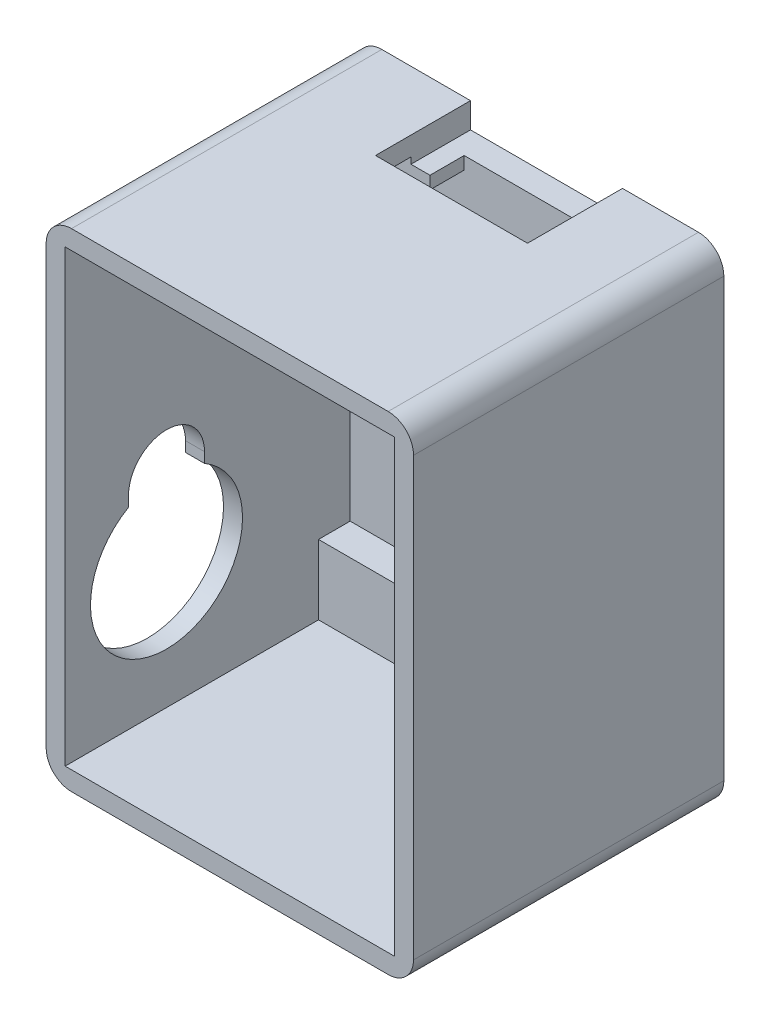
SolidWorks part; units mm, degrees
ref_plane "前视基准面" through (0, 0, 0) normal (0, 0, 1) x (1, 0, 0)
ref_plane "上视基准面" through (0, 0, 0) normal (0, 1, 0) x (1, 0, 0)
ref_plane "右视基准面" through (0, 0, 0) normal (1, 0, 0) x (0, 0, -1)
sketch "草图1" plane through (0, 0, 0) normal (0, 0, 1) x (1, 0, 0)
  line L1 (0, 0) -> (29, 0)
  line L2 (0, 0) -> (0, -38.5)
  line L3 (0, -38.5) -> (29, -38.5)
  line L4 (29, 0) -> (29, -38.5)
extrude "凸台-拉伸1" add sketch "草图1" along normal blind 24
shell "抽壳1" thickness 1.5
sketch "草图2" plane through (0, 0, 0) normal (0, 0, -1) x (-1, 0, 0)
  line L0 (-29, 0) -> (0, 0) construction
  line L1 (-21, 0) -> (-9, 0)
  line L2 (-21, 0) -> (-21, -2)
  line L3 (-21, -2) -> (-9, -2)
  line L4 (-9, 0) -> (-9, -2)
  line L5 (-29, -38.5) -> (-29, 0) construction
  line L6 (0, 0) -> (0, -38.5) construction
  dimension "D1" = 8
  dimension "D2" = 9
sketch "草图5" plane through (27.5, 0, 0) normal (-1, 0, 0) x (0, 0, 1)
  line L0 (24, -1.5) -> (1.5, -1.5) construction
  line L1 (4.2, -1.5) -> (1.5, -1.5)
  line L2 (4.2, -1.5) -> (4.2, -3)
  line L3 (4.2, -3) -> (1.5, -3)
  line L4 (1.5, -1.5) -> (1.5, -3)
  line L5 (1.5, -37) -> (1.5, -1.5) construction
sketch "草图6" plane through (1.5, 0, 0) normal (1, 0, 0) x (0, 0, -1)
  line L0 (-24, -1.5) -> (-1.5, -1.5) construction
  line L1 (-4.2, -1.5) -> (-1.5, -1.5)
  line L2 (-4.2, -1.5) -> (-4.2, -3)
  line L3 (-4.2, -3) -> (-1.5, -3)
  line L4 (-1.5, -1.5) -> (-1.5, -3)
  line L5 (-1.5, -1.5) -> (-1.5, -37) construction
sketch "草图7" plane through (0, 0, 1.5) normal (0, 0, 1) x (1, 0, 0)
  line L0 (27.5, -37) -> (27.5, -1.5) construction
  line L1 (27.5, -31.5) -> (1.5, -31.5)
  line L2 (27.5, -31.5) -> (27.5, -37)
  line L3 (27.5, -37) -> (1.5, -37)
  line L4 (1.5, -31.5) -> (1.5, -37)
  line L5 (1.5, -37) -> (27.5, -37) construction
extrude "凸台-拉伸7" add sketch "草图7" along normal blind 2.5
extrude "凸台-拉伸8" add sketch "草图5" along normal blind 8
extrude "凸台-拉伸9" add sketch "草图6" along normal blind 9
sketch "草图8" plane through (0, 0, 0) normal (-1, 0, 0) x (0, 0, 1)
  line L0 (0, 0) -> (0, -38.5) construction
  line L1 (24, -37) -> (4, -37) construction
  line L2 (19, -21) -> (19, -21.8038)
  line L3 (13, -21) -> (13, -21.8038)
  arc A0 (13, -21.8038) -> (19, -21.8038) centre (16, -27) ccw
  arc A1 (19, -21) -> (13, -21) centre (16, -21) ccw
  dimension "D1" = 16
  dimension "D3" = 6
  dimension "D2" = 10
extrude "切除-拉伸7" cut sketch "草图8" against normal blind 1.5
sketch "草图9" plane through (0, 0, 0) normal (0, 0, -1) x (-1, 0, 0)
  line L1 (0, 0) -> (-29, 0)
  line L2 (0, 0) -> (0, -38.5)
  line L3 (0, -38.5) -> (-29, -38.5)
  line L4 (-29, 0) -> (-29, -38.5)
extrude "凸台-拉伸10" add sketch "草图9" along normal blind 0.5
fillet "圆角3" radius 2 4 edges at (29, 0, 11.75) (29, -38.5, 11.75) (0, -38.5, 11.75) (0, 0, 11.75)
extrude "切除-拉伸8" cut sketch "草图2" against normal blind 7 and the other way blind 1.5
